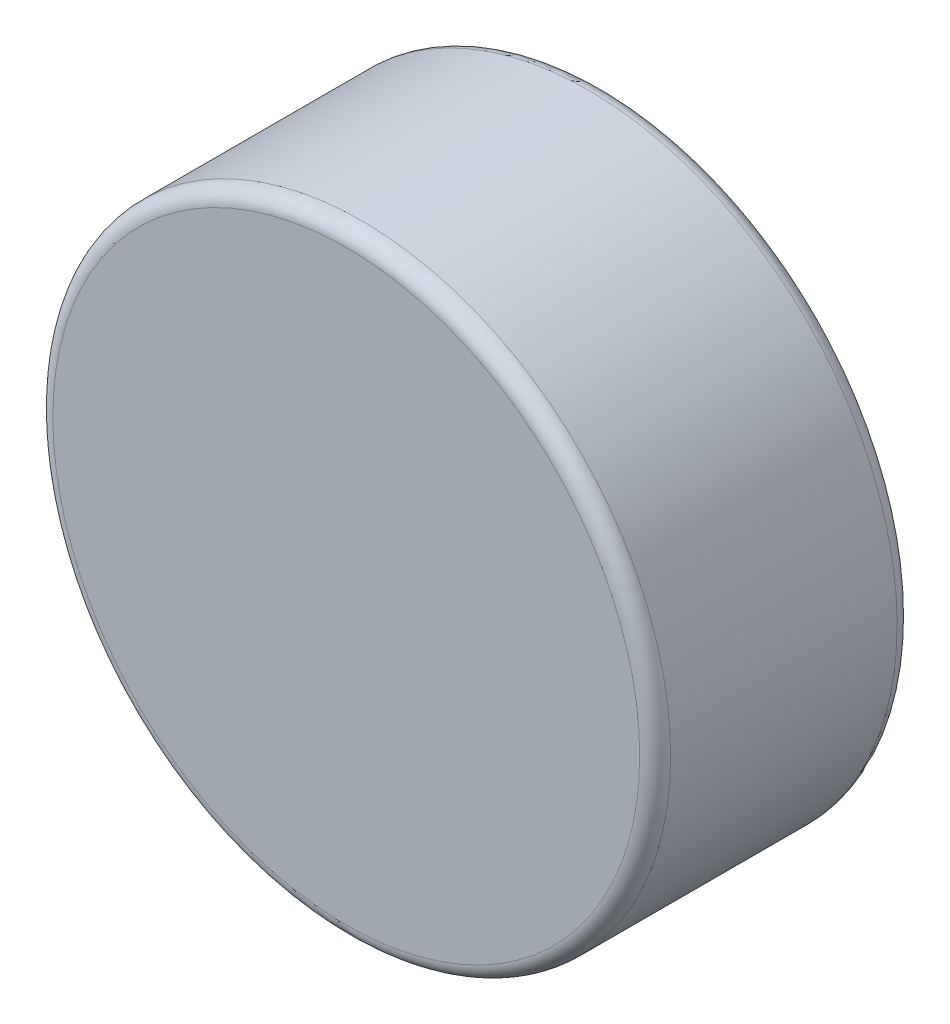
SolidWorks part; units mm, degrees
ref_plane "Přední rovina" through (0, 0, 0) normal (0, 0, 1) x (1, 0, 0)
ref_plane "Horní rovina" through (0, 0, 0) normal (0, 1, 0) x (1, 0, 0)
ref_plane "Pravá rovina" through (0, 0, 0) normal (1, 0, 0) x (0, 0, -1)
sketch "Skica1" plane through (0, 0, 0) normal (0, 0, 1) x (1, 0, 0)
  circle A0 centre (0, 0) radius 3
  dimension "D1" = 6
extrude "Přidat vysunutím1" add sketch "Skica1" along normal blind 2.5
fillet "Zaoblit1" radius 0.15 2 edges at (3, 0, 0) (3, 0, 2.5)
